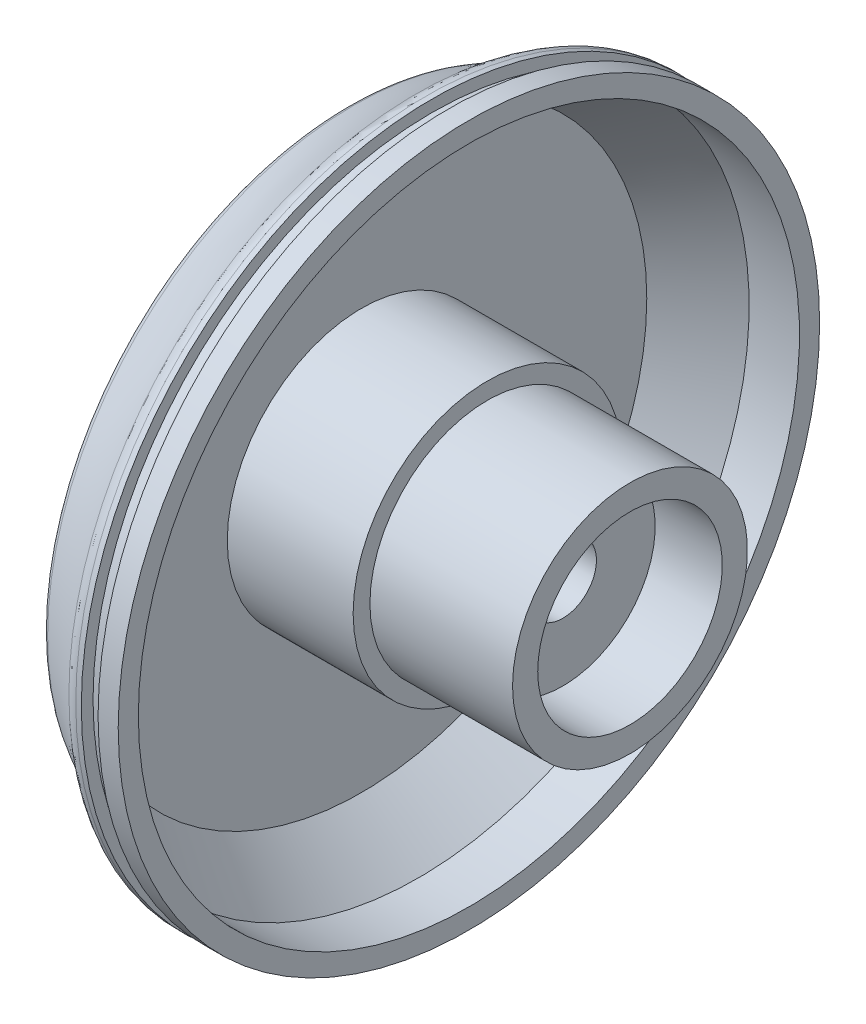
SolidWorks part; units mm, degrees
ref_plane "Front Plane" through (0, 0, 0) normal (0, 0, 1) x (1, 0, 0)
ref_plane "Top Plane" through (0, 0, 0) normal (0, 1, 0) x (1, 0, 0)
ref_plane "Right Plane" through (0, 0, 0) normal (1, 0, 0) x (0, 0, -1)
sketch "Sketch1" plane through (0, 0, 0) normal (0, 0, 1) x (1, 0, 0)
  line L0 (0, 209) -> (0, 0) construction
  line L1 (0, 0) -> (250.2589, 0) construction
  line L2 (170, 55) -> (130, 55)
  line L3 (130, 55) -> (130, 20)
  line L4 (130, 20) -> (40, 20)
  line L5 (40, 20) -> (40, 55)
  line L6 (40, 55) -> (0, 55)
  line L7 (0, 55) -> (0, 180)
  line L8 (45, 209) -> (52, 209)
  line L9 (74, 209) -> (74, 197)
  line L10 (74, 197) -> (44, 197)
  line L11 (44, 197) -> (10, 170)
  line L12 (10, 170) -> (10, 80)
  line L13 (10, 80) -> (85, 80)
  line L14 (85, 80) -> (85, 70)
  line L15 (85, 70) -> (170, 70)
  line L16 (170, 70) -> (170, 55)
  line L17 (40, 55) -> (130, 55) construction
  line L18 (62, 209) -> (74, 209)
  line L20 (52, 209) -> (52, 202)
  line L21 (52, 202) -> (62, 202)
  line L22 (62, 209) -> (62, 202)
  arc A1 (0, 180) -> (45, 209) centre (-75.2366, 346.1602) ccw
  point P16 (85, 75)
  point P22 (0, 117.5)
  dimension "D21" = 182.4
  dimension "D1" = 209
  dimension "D2" = 170
  dimension "D3" = 20
  dimension "D4" = 70
  dimension "D5" = 80
  dimension "D6" = 40
  dimension "D7" = 45
  dimension "D8" = 40
  dimension "D9" = 55
  dimension "D10" = 55
  dimension "D11" = 10
  dimension "D12" = 29
  dimension "D13" = 30
  dimension "D14" = 45
  dimension "D15" = 12
  dimension "D16" = 180
  dimension "D17" = 90
  dimension "D18" = 7
  dimension "D19" = 10
  dimension "D20" = 7
revolve "Revolve1" add sketch "Sketch1" angle 360 about L1
fillet "Fillet1" radius 10 2 edges at (45, 0, 209) (0, 0, 180)
